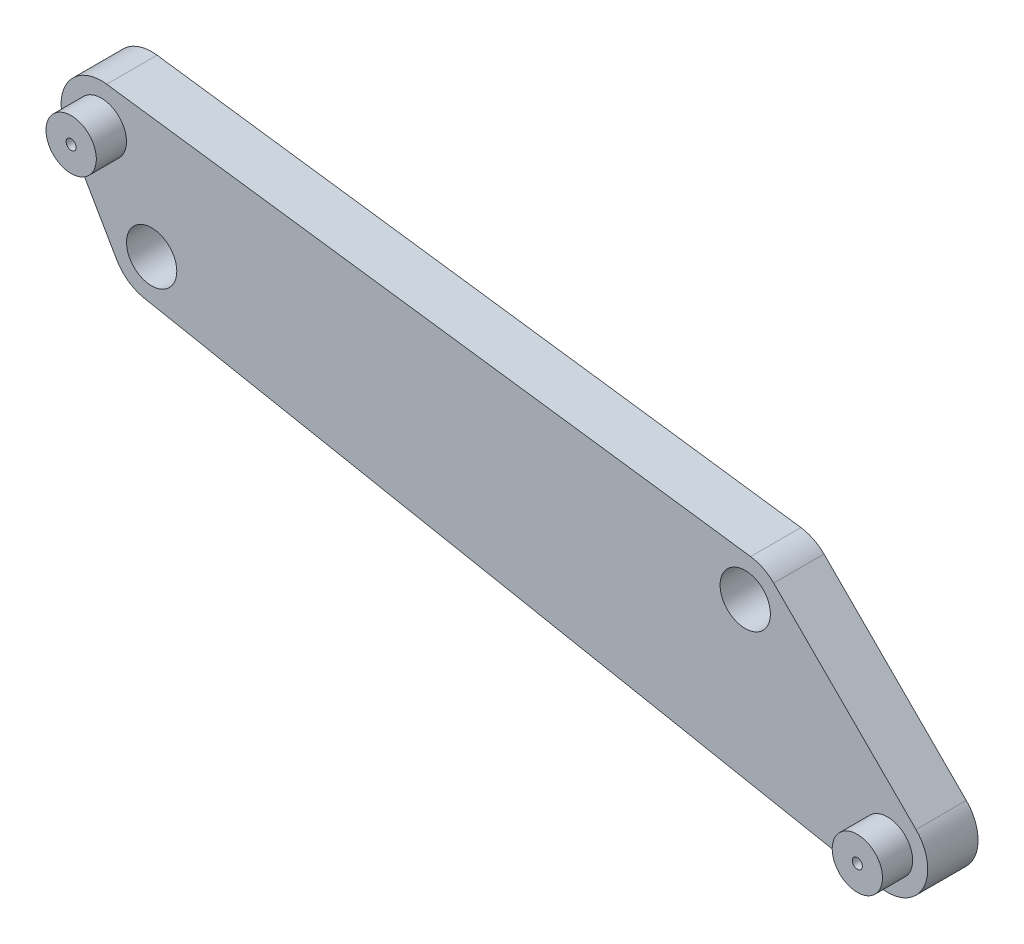
SolidWorks part; units mm, degrees
material "ABS"
ref_plane "Front Plane" through (0, 0, 0) normal (0, 0, 1) x (1, 0, 0)
ref_plane "Top Plane" through (0, 0, 0) normal (0, 1, 0) x (1, 0, 0)
ref_plane "Right Plane" through (0, 0, 0) normal (1, 0, 0) x (0, 0, -1)
sketch "Sketch1" plane through (0, 0, 0) normal (0, 0, 1) x (1, 0, 0)
  line L0 (0, 0) -> (-59, 0)
  line L1 (-59, 0) -> (-64, 8.6603)
  line L2 (0, 0) -> (14.1421, -14.1421)
  dimension "D1" = 59
  dimension "D2" = 10
  dimension "D3" = 20
  dimension "D4" = 120
  dimension "D5" = 135
sketch "Sketch2" plane through (0, 0, 0) normal (0, 0, 1) x (1, 0, 0)
  line L0 (-63.4636, 12.6241) -> (0.5364, 3.9639)
  line L1 (2.8284, 2.8284) -> (16.9706, -11.3137)
  line L2 (13.3828, -18.0694) -> (-59.7593, -3.9273)
  line L3 (-62.4641, -2) -> (-67.4641, 6.6603)
  circle A0 centre (-59, 0) radius 2.5
  circle A1 centre (-64, 8.6603) radius 2.5
  arc A2 (-63.4636, 12.6241) -> (-67.4641, 6.6603) centre (-64, 8.6603) ccw
  arc A3 (-62.4641, -2) -> (-59.7593, -3.9273) centre (-59, 0) ccw
  circle A4 centre (0, 0) radius 2.5
  circle A5 centre (14.1421, -14.1421) radius 2.5
  arc A6 (2.8284, 2.8284) -> (0.5364, 3.9639) centre (0, 0) ccw
  arc A7 (13.3828, -18.0694) -> (16.9706, -11.3137) centre (14.1421, -14.1421) ccw
  dimension "D1" = 5
  dimension "D2" = 5
  dimension "D3" = 5
  dimension "D4" = 5
  dimension "D5" = 8
  dimension "D6" = 8
  dimension "D7" = 8
  dimension "D8" = 8
extrude "Boss-Extrude1" add sketch "Sketch2" along normal blind 5
sketch "Sketch4" plane through (0, 0, 0) normal (0, 0, -1) x (-1, 0, 0)
  circle A0 centre (64, 8.6603) radius 2.5
  circle A1 centre (64, 8.6603) radius 0.5
  circle A2 centre (-14.1421, -14.1421) radius 2.5
  circle A3 centre (-14.1421, -14.1421) radius 0.5
  dimension "D1" = 1
  dimension "D2" = 5
  dimension "D3" = 5
  dimension "D4" = 1
extrude "Boss-Extrude3" add sketch "Sketch4" against normal blind 8
